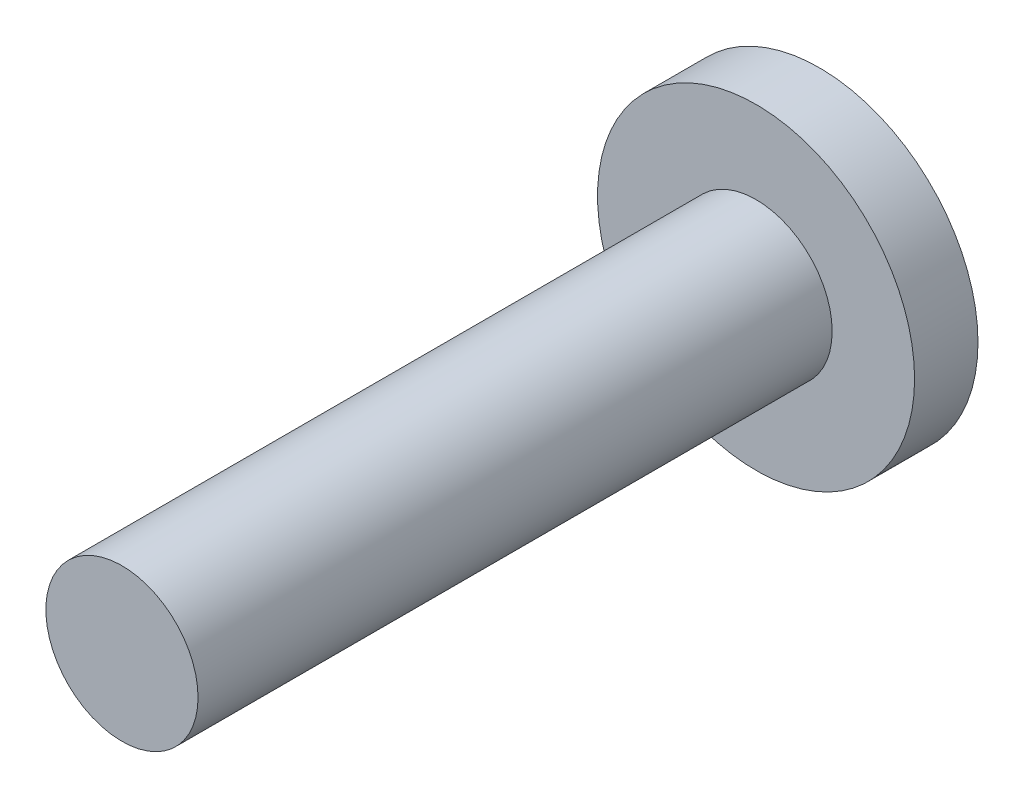
SolidWorks part; units mm, degrees
material "AISI 304"
ref_plane "前视基准面" through (0, 0, 0) normal (0, 0, 1) x (1, 0, 0)
ref_plane "上视基准面" through (0, 0, 0) normal (0, 1, 0) x (1, 0, 0)
ref_plane "右视基准面" through (0, 0, 0) normal (1, 0, 0) x (0, 0, -1)
other "Configuration Table"
sketch "草图1" plane through (0, 0, 0) normal (0, 0, 1) x (1, 0, 0)
  circle A0 centre (0, 0) radius 6.25
  dimension "D1" = 12.5
extrude "凸台-拉伸1" add sketch "草图1" along normal blind 2.5
sketch "草图2" plane through (0, 0, 2.5) normal (0, 0, 1) x (1, 0, 0)
  circle A0 centre (0, 0) radius 3
  dimension "D1" = 6
extrude "凸台-拉伸2" add sketch "草图2" along normal blind 25
sketch "草图3" plane through (0, 0, 0) normal (0, 0, -1) x (-1, 0, 0)
  line L1 (2.3094, 0) -> (1.1547, 2)
  line L2 (1.1547, 2) -> (-1.1547, 2)
  line L3 (-1.1547, 2) -> (-2.3094, 0)
  line L4 (-2.3094, 0) -> (-1.1547, -2)
  line L5 (-1.1547, -2) -> (1.1547, -2)
  line L6 (1.1547, -2) -> (2.3094, 0)
  circle A0 centre (0, 0) radius 2 construction
extrude "切除-拉伸1" cut sketch "草图3" against normal blind 1
